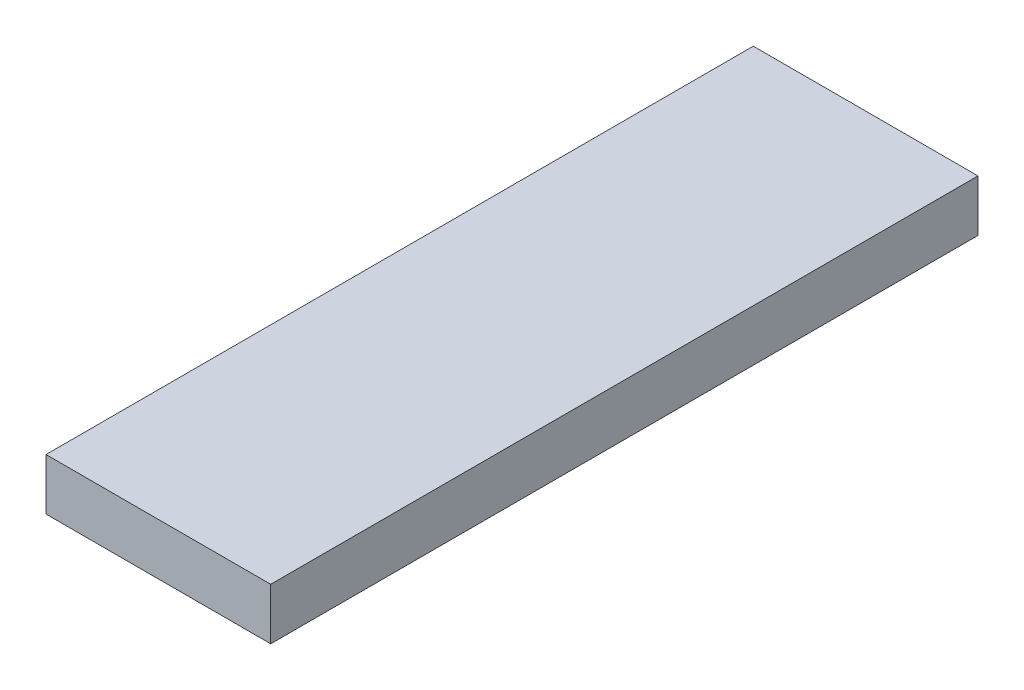
SolidWorks part; units mm, degrees
material "A-Glass Fiber"
ref_plane "Front Plane" through (0, 0, 0) normal (0, 0, 1) x (1, 0, 0)
ref_plane "Top Plane" through (0, 0, 0) normal (0, 1, 0) x (1, 0, 0)
ref_plane "Right Plane" through (0, 0, 0) normal (1, 0, 0) x (0, 0, -1)
sketch "Sketch1" plane through (0, 0, 0) normal (0, 1, 0) x (1, 0, 0)
  line L1 (-193.675, 609.6) -> (193.675, 609.6)
  line L2 (-193.675, 609.6) -> (-193.675, -609.6)
  line L3 (-193.675, -609.6) -> (193.675, -609.6)
  line L4 (193.675, 609.6) -> (193.675, -609.6)
  line L5 (-193.675, 609.6) -> (193.675, -609.6) construction
  line L6 (-193.675, -609.6) -> (193.675, 609.6) construction
  point P0 (0, 0)
  dimension "D1" = 387.35
  dimension "D2" = 1219.2
extrude "Boss-Extrude1" add sketch "Sketch1" along normal blind 88.9
